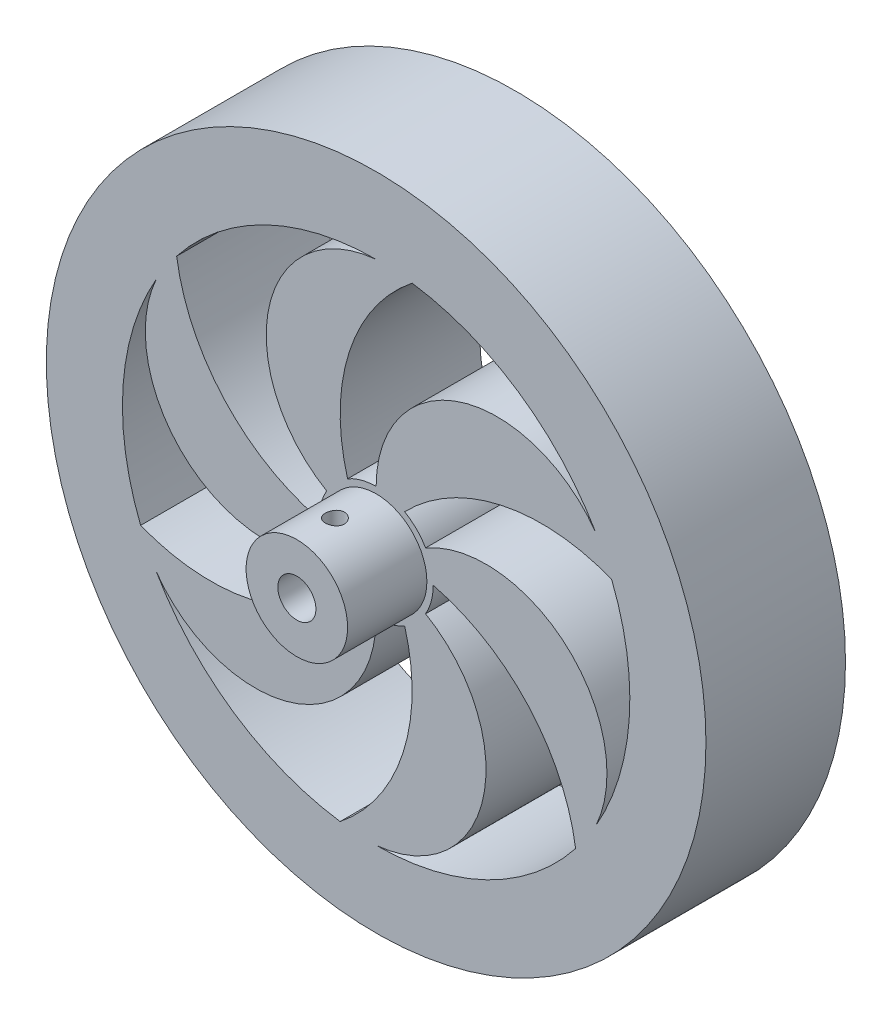
SolidWorks part; units mm, degrees
ref_plane "Front Plane" through (0, 0, 0) normal (0, 0, 1) x (1, 0, 0)
ref_plane "Top Plane" through (0, 0, 0) normal (0, 1, 0) x (1, 0, 0)
ref_plane "Right Plane" through (0, 0, 0) normal (1, 0, 0) x (0, 0, -1)
sketch "Sketch1" plane through (0, 0, 0) normal (0, 0, 1) x (1, 0, 0)
  circle A0 centre (0, 0) radius 52
  dimension "D1" = 104
extrude "wheel" add sketch "Sketch1" along normal blind 22
sketch "Sketch2" plane through (0, 0, 22) normal (0, 0, 1) x (1, 0, 0)
  circle A0 centre (0, 0) radius 8
  dimension "D1" = 16
extrude "boss" add sketch "Sketch2" along normal blind 12.5
sketch "Sketch3" plane through (0, 0, 34.5) normal (0, 0, 1) x (1, 0, 0)
  circle A0 centre (0, 0) radius 3
  dimension "D1" = 6
extrude "bore" cut sketch "Sketch3" against normal blind 12.3
sketch "Sketch4" plane through (0, 0, 0) normal (0, 1, 0) x (1, 0, 0)
  line L0 (-8, -34.5) -> (8, -34.5) construction
  circle A0 centre (0, -28.5) radius 1.5
  dimension "D1" = 3
  dimension "D2" = 6
extrude "grub screw hole" cut sketch "Sketch4" along normal through all
sketch "Sketch5" plane through (0, 0, 0) normal (0, 0, -1) x (-1, 0, 0)
  line L0 (-11.5412, -6.6633) -> (42.1255, 24.3212) construction
  line L1 (0, 0) -> (0, 40) construction
  line L2 (0, 0) -> (9, 0) construction
  line L3 (-50.7942, -29.326) -> (50.7942, 29.326) construction
  arc A0 (7.7942, 4.5) -> (0, 40) centre (-1.7393, 21.0125) ccw
  arc A1 (31.4517, 24.7142) -> (9, 0) centre (1.7766, 29.1174) cw
  arc A2 (0, 40) -> (31.4517, 24.7142) centre (0, 0) cw
  arc A3 (7.7942, 4.5) -> (9, 0) centre (0, 0) cw
  point P10 (29.3358, 27.1921)
  point P13 (4.8492, 32.0821)
  point P14 (31.4517, 24.7142)
  dimension "D4" = 30
  dimension "D5" = 30
  dimension "D1" = 40
  dimension "D2" = 60
  dimension "D3" = 9
  dimension "D6" = 60
extrude "spoke cut" cut sketch "Sketch5" against normal through all
pattern_circular "spokes cut" count 6 over 360 about axis through (0, 0, 0) along (0, 0, 1) of "spoke cut"
ref_plane "ground contact" through (0, -52, 0) normal (0, 1, 0) x (1, 0, 0)
